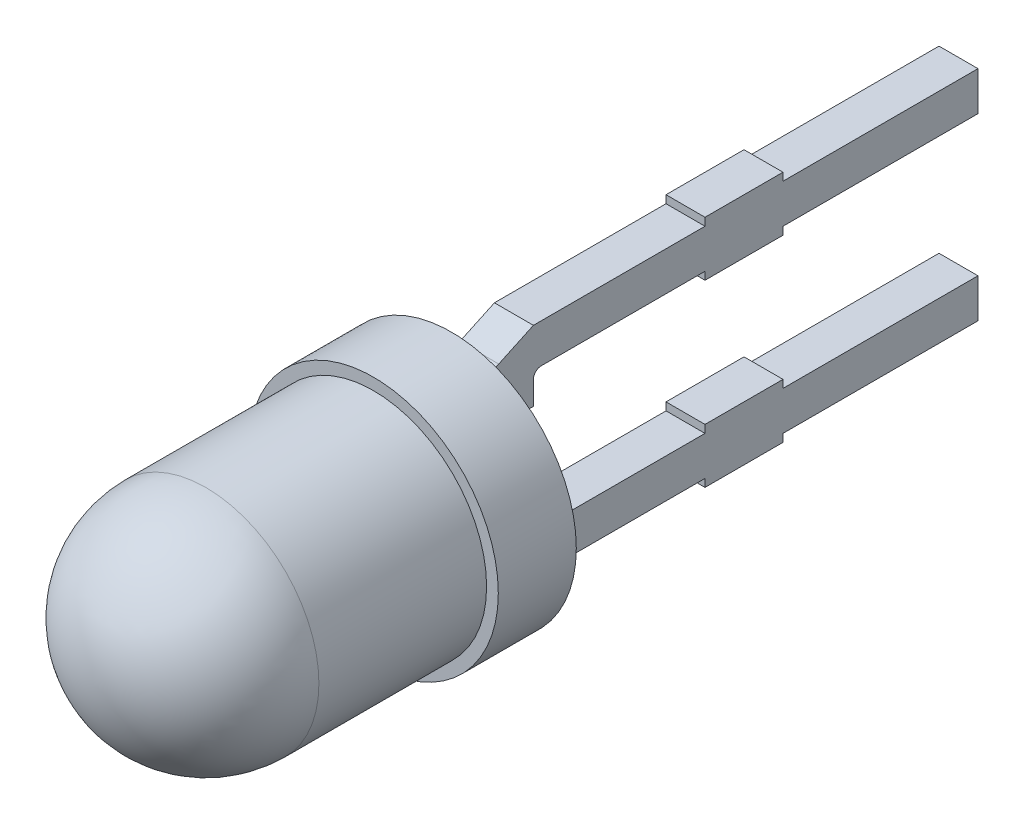
SolidWorks part; units mm, degrees
ref_plane "Front" through (0, 0, 0) normal (0, 0, 1) x (1, 0, 0)
ref_plane "Top" through (0, 0, 0) normal (0, 1, 0) x (1, 0, 0)
ref_plane "Right" through (0, 0, 0) normal (1, 0, 0) x (0, 0, -1)
sketch "Sketch1" plane through (0, 0, 0) normal (1, 0, 0) x (0, 0, -1)
  line L0 (0, 0) -> (76.2974, 0) construction
  line L1 (0, 1.45) -> (2.15, 1.45)
  line L2 (2.15, 1.45) -> (2.15, 1.6)
  line L3 (2.15, 1.6) -> (3.15, 1.6)
  line L4 (3.15, 1.6) -> (3.15, 0)
  line L5 (3.15, 0) -> (-1.45, 0)
  arc A0 (0, 1.45) -> (-1.45, 0) centre (0, 0) ccw
  dimension "D1" = 1.45
  dimension "D2" = 4.6
  dimension "D3" = 1
  dimension "D4" = 1.6
revolve "Revolve1" add sketch "Sketch1" angle 360 about L0
sketch "Sketch2" plane through (0, 0, 0) normal (1, 0, 0) x (0, 0, -1)
  line L0 (3.15, -1.6) -> (3.15, 1.6) construction
  line L1 (3.15, -1.6) -> (3.15, 1.6) construction
  line L2 (3.15, 1.027) -> (3.95, 1.4)
  line L3 (3.95, 1.4) -> (6.15, 1.4)
  line L4 (6.15, 1.4) -> (6.15, 1.5)
  line L5 (6.15, 1.5) -> (7.15, 1.5)
  line L6 (7.15, 1.5) -> (7.15, 1.4)
  line L7 (7.15, 1.4) -> (30.15, 1.4)
  line L8 (30.15, 1.4) -> (30.15, 0.9)
  line L9 (30.15, 0.9) -> (7.15, 0.9)
  line L10 (7.15, 0.9) -> (7.15, 0.8)
  line L11 (7.15, 0.8) -> (6.15, 0.8)
  line L12 (6.15, 0.8) -> (6.15, 0.9)
  line L13 (6.15, 0.9) -> (4.05, 0.9)
  line L14 (3.95, 0.8) -> (3.95, 0.5)
  line L15 (3.95, 0.5) -> (3.15, 0.5)
  line L16 (3.15, 0) -> (7.9733, 0) construction
  line L17 (3.15, 1.027) -> (3.15, 0.5)
  line L18 (3.95, -0.8) -> (3.95, -0.5)
  line L19 (6.15, -0.9) -> (4.05, -0.9)
  line L20 (6.15, -0.8) -> (6.15, -0.9)
  line L21 (7.15, -0.8) -> (6.15, -0.8)
  line L22 (7.15, -0.9) -> (7.15, -0.8)
  line L23 (30.15, -0.9) -> (7.15, -0.9)
  line L24 (30.15, -1.4) -> (30.15, -0.9)
  line L25 (7.15, -1.4) -> (30.15, -1.4)
  line L26 (7.15, -1.5) -> (7.15, -1.4)
  line L27 (6.15, -1.5) -> (7.15, -1.5)
  line L28 (6.15, -1.4) -> (6.15, -1.5)
  line L29 (3.95, -1.4) -> (6.15, -1.4)
  line L30 (3.15, -1.027) -> (3.95, -1.4)
  line L31 (3.15, -1.027) -> (3.15, -0.5)
  line L32 (3.95, -0.5) -> (3.15, -0.5)
  arc A0 (4.05, 0.9) -> (3.95, 0.8) centre (4.05, 0.8) ccw
  arc A1 (4.05, -0.9) -> (3.95, -0.8) centre (4.05, -0.8) cw
  point P19 (3.15, 0)
  dimension "D1" = 0.5
  dimension "D2" = 0.7
  dimension "D3" = 1.4
  dimension "D4" = 0.8
  dimension "D5" = 27
  dimension "D6" = 115
  dimension "D7" = 4
  dimension "D8" = 1
  dimension "D9" = 0.5
  dimension "D10" = 0.1
extrude "Extrude1" add sketch "Sketch2" along normal mid plane 0.5
fillet "Fillet1" radius 0.25 8 edges at (0, -0.5, -3.15) (0, -1.027, -3.15) (-0.25, -0.7635, -3.15) (0, 0.5, -3.15) (-0.25, 0.7635, -3.15) (0, 1.027, -3.15) (0.25, 0.7635, -3.15) (0.25, -0.7635, -3.15)
sketch "Sketch3" plane through (0, 0, 0) normal (1, 0, 0) x (0, 0, -1)
  line L0 (3.15, -1.6) -> (3.15, 1.6) construction
  line L1 (9.65, 3.4296) -> (31.1569, 3.4296)
  line L2 (9.65, 3.4296) -> (9.65, -3.457)
  line L3 (9.65, -3.457) -> (31.1569, -3.457)
  line L4 (31.1569, 3.4296) -> (31.1569, -3.457)
  dimension "D1" = 6.5
extrude "Cut-Extrude1" cut sketch "Sketch3" against normal through all both and the other way through all
